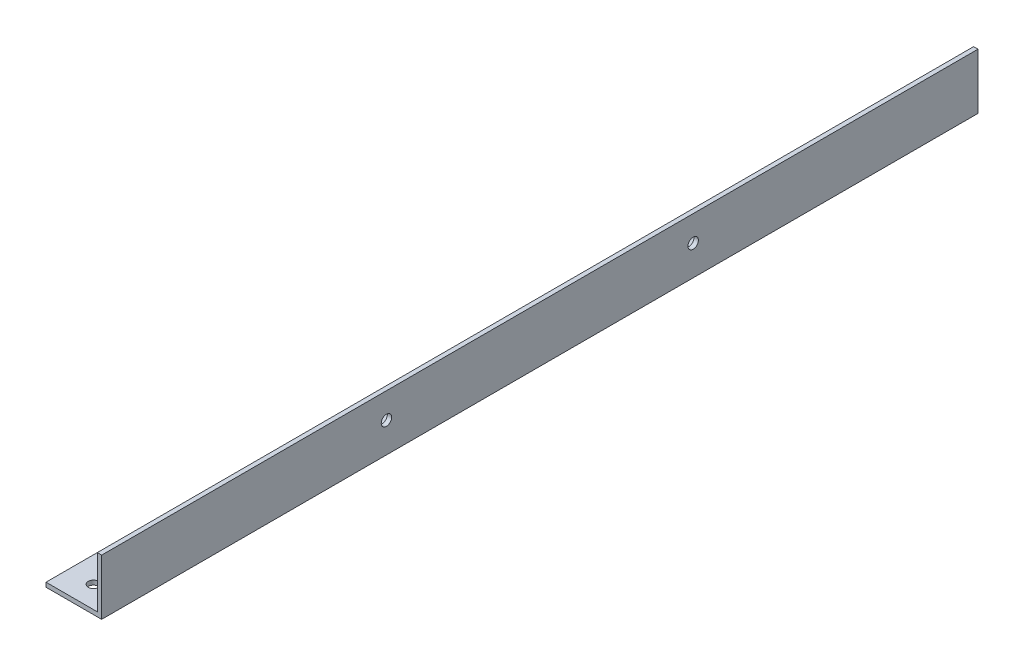
SolidWorks part; units mm, degrees
material "1060 Alloy"
ref_plane "Front Plane" through (0, 0, 0) normal (0, 0, 1) x (1, 0, 0)
ref_plane "Top Plane" through (0, 0, 0) normal (0, 1, 0) x (1, 0, 0)
ref_plane "Right Plane" through (0, 0, 0) normal (1, 0, 0) x (0, 0, -1)
sketch "Sketch1" plane through (0, 0, 0) normal (0, 0, 1) x (1, 0, 0)
  line L0 (-6.389, -3.9695) -> (5.311, -3.9695)
  line L1 (5.311, -3.9695) -> (5.311, 7.7305)
  line L2 (5.311, 7.7305) -> (6.311, 7.7305)
  line L3 (6.311, 7.7305) -> (6.311, -4.9695)
  line L4 (6.311, -4.9695) -> (-6.389, -4.9695)
  line L5 (-6.389, -4.9695) -> (-6.389, -3.9695)
  dimension "D1" = 12.7
  dimension "D2" = 12.7
  dimension "D3" = 1
  dimension "D4" = 1
extrude "Boss-Extrude1" add sketch "Sketch1" along normal blind 200
hole_wizard "3/32 (0.09375) Diameter Hole1" positions "Sketch4" profile "Sketch3" hole size "3/32" standard "ANSI Inch"
sketch "Sketch4" plane through (0, -3.9695, 0) normal (0, 1, 0) x (1, 0, 0)
  line L0 (5.311, -200) -> (-6.389, -200) construction
  line L1 (-6.389, -200) -> (-6.389, 0) construction
  point P0 (-0.539, -4.9709)
  point P2 (-0.539, -100)
  point P4 (-0.539, -195)
  dimension "D1" = 5
  dimension "D2" = 5
  dimension "D3" = 5.85
  dimension "D4" = 5.85
  dimension "D5" = 5.85
sketch "Sketch3" plane through (-0.539, -3.9695, 4.9709) normal (1, 0, 0) x (0, 0, 1)
  line L0 (0, 0) -> (0, 5.7154)
  line L1 (0, 5.7154) -> (1.1906, 5)
  line L2 (1.1906, 5) -> (1.1906, 0)
  line L5 (1.1906, 0) -> (0, 0)
  line L10 (0, 5.7154) -> (-1.1906, 5) construction
  line L11 (0, -6.35) -> (0, 107.95) construction
  dimension "Hole Dia." = 2.3812
  dimension "Hole Depth" = 5
  dimension "Drill Angle" = 118
hole_wizard "3/32 (0.09375) Diameter Hole2" positions "Sketch9" profile "Sketch8" hole size "3/32" standard "ANSI Inch"
sketch "Sketch9" plane through (5.311, 0, 0) normal (-1, 0, 0) x (0, 0, 1)
  line L0 (200, 7.7305) -> (0, 7.7305) construction
  line L1 (0, 7.7305) -> (0, -3.9695) construction
  line L2 (200, 7.7305) -> (200, -3.9695) construction
  point P0 (65, 1.8805)
  point P2 (135, 1.8805)
  dimension "D1" = 5.85
  dimension "D2" = 5.85
  dimension "D3" = 65
  dimension "D4" = 65
sketch "Sketch8" plane through (5.311, 1.8805, 65) normal (0, 1, 0) x (0, 0, 1)
  line L0 (0, 0) -> (0, 5.7154)
  line L1 (0, 5.7154) -> (1.1906, 5)
  line L2 (1.1906, 5) -> (1.1906, 0)
  line L5 (1.1906, 0) -> (0, 0)
  line L10 (0, 5.7154) -> (-1.1906, 5) construction
  line L11 (0, -6.35) -> (0, 107.95) construction
  dimension "Hole Dia." = 2.3812
  dimension "Hole Depth" = 5
  dimension "Drill Angle" = 118
